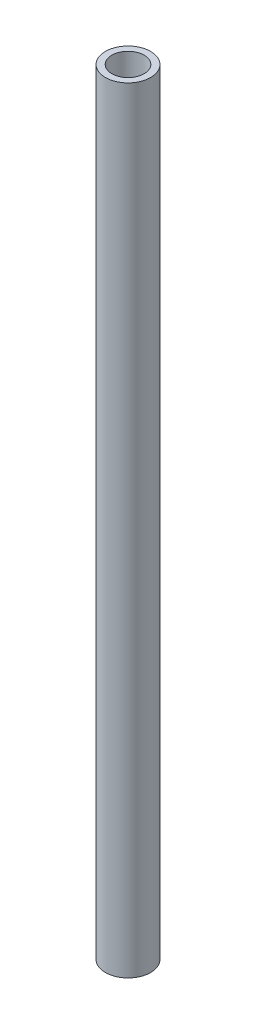
SolidWorks part; units mm, degrees
ref_plane "Front Plane" through (0, 0, 0) normal (0, 0, 1) x (1, 0, 0)
ref_plane "Top Plane" through (0, 0, 0) normal (0, 1, 0) x (1, 0, 0)
ref_plane "Right Plane" through (0, 0, 0) normal (1, 0, 0) x (0, 0, -1)
sketch "Sketch1" plane through (0, 0, 0) normal (0, 0, 1) x (1, 0, 0)
  line L0 (-62.594, 0) -> (62.594, 0) construction
  line L1 (0, -84.5865) -> (0, 84.5865) construction
  line L2 (2.5, 60) -> (2.5, -60)
  line L6 (2.5, 60) -> (3.5, 60)
  line L7 (3.5, 60) -> (3.5, -60)
  line L8 (3.5, -60) -> (2.5, -60)
  point P7 (2.5, 0)
  dimension "D1" = 120
  dimension "D2" = 5
  dimension "D3" = 1
revolve "Revolve1" add sketch "Sketch1" angle 360 about L1
